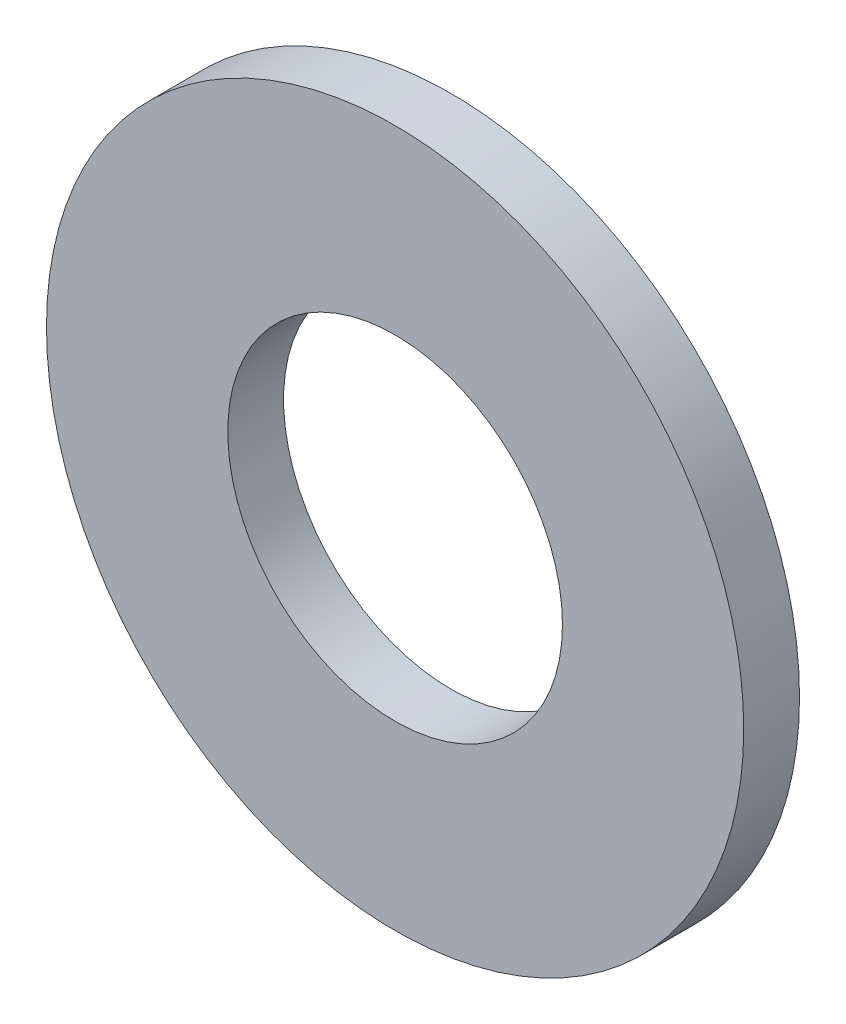
SolidWorks part; units mm, degrees
ref_plane "前视基准面" through (0, 0, 0) normal (0, 0, 1) x (1, 0, 0)
ref_plane "上视基准面" through (0, 0, 0) normal (0, 1, 0) x (1, 0, 0)
ref_plane "右视基准面" through (0, 0, 0) normal (1, 0, 0) x (0, 0, -1)
sketch "Sketch1" plane through (0, 0, 0) normal (0, 0, 1) x (1, 0, 0)
  circle A0 centre (0, 0) radius 6
  circle A1 centre (0, 0) radius 12.5
  dimension "D1" = 12
  dimension "D2" = 25
extrude "Extrude1" add sketch "Sketch1" along normal blind 2
